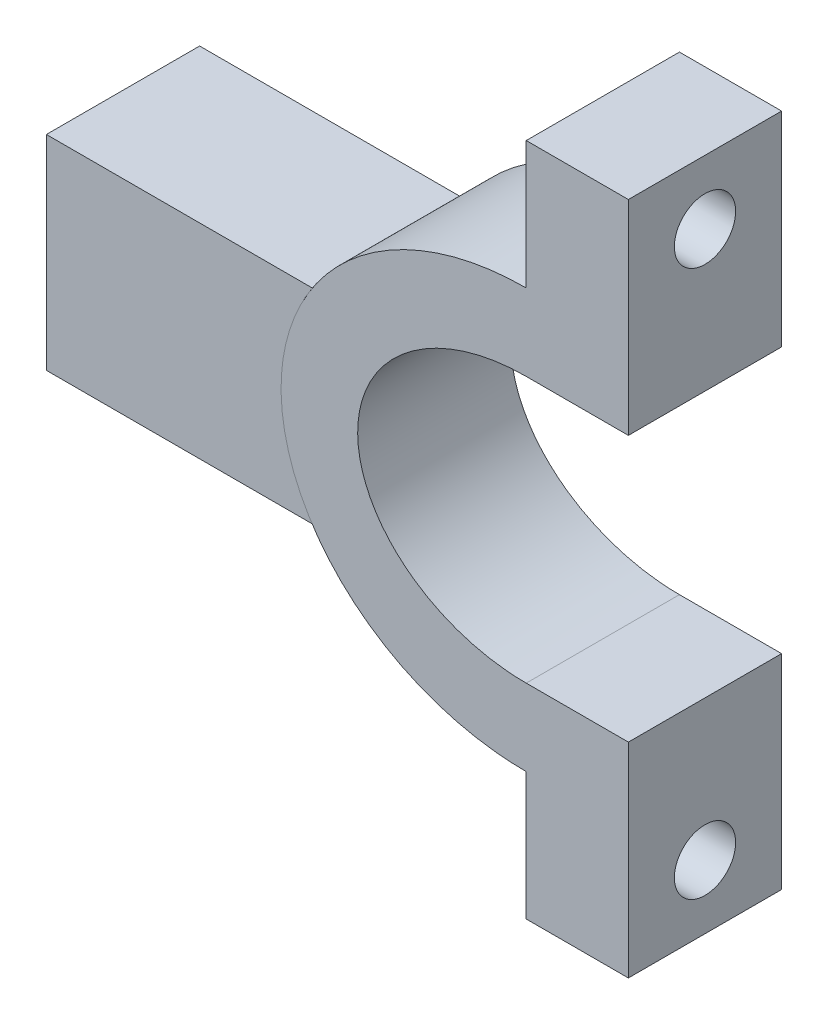
SolidWorks part; units mm, degrees
ref_plane "Front Plane" through (0, 0, 0) normal (0, 0, 1) x (1, 0, 0)
ref_plane "Top Plane" through (0, 0, 0) normal (0, 1, 0) x (1, 0, 0)
ref_plane "Right Plane" through (0, 0, 0) normal (1, 0, 0) x (0, 0, -1)
sketch "Sketch1" plane through (0, 0, 0) normal (0, 0, 1) x (1, 0, 0)
  line L0 (0, 20.5) -> (0, -20.5)
  ellipse E0 centre (0, 0) end of major axis (16.5, 0) minor radius 13
  ellipse E1 centre (0, 0) end of major axis (24, 0) minor radius 20.5
  dimension "D1" = 26
  dimension "D2" = 33
  dimension "D3" = 41
  dimension "D4" = 48
extrude "Boss-Extrude1" add sketch "Sketch1" along normal blind 15 contours L0 E1 E0
ref_plane "Plane1" through (-24, 0, 0) normal (1, 0, 0) x (0, 0, -1)
sketch "Sketch2" plane through (-24, 0, 0) normal (1, 0, 0) x (0, 0, -1)
  line L2 (0.0273, 10) -> (-14.9727, 10)
  line L3 (0.0273, 10) -> (0.0273, -10)
  line L4 (0.0273, -10) -> (-14.9727, -10)
  line L5 (-14.9727, 10) -> (-14.9727, -10)
  line L6 (0.0273, 10) -> (-14.9727, -10) construction
  line L7 (0.0273, -10) -> (-14.9727, 10) construction
  point P2 (-7.4727, 0)
  dimension "D1" = 15
  dimension "D2" = 20
extrude "Boss-Extrude2" add sketch "Sketch2" against normal blind 23 and the other way blind 5
sketch "Sketch3" plane through (0, 0, 0) normal (1, 0, 0) x (0, 0, -1)
  line L0 (0, 0) -> (-15, 0) construction
  line L1 (-15, 13) -> (0, 13)
  line L2 (-15, 13) -> (-15, 33)
  line L3 (-15, 33) -> (0, 33)
  line L4 (0, 13) -> (0, 33)
  line L5 (-15, 13) -> (-15, -13) construction
  line L6 (-15, -33) -> (0, -33)
  line L7 (0, -13) -> (0, -33)
  line L8 (-15, -13) -> (0, -13)
  line L9 (-15, -13) -> (-15, -33)
  dimension "D1" = 20
extrude "Boss-Extrude3" add sketch "Sketch3" along normal blind 10
sketch "Sketch4" plane through (0, 0, 0) normal (-1, 0, 0) x (0, 0, 1)
  line L0 (0, 33) -> (15, 20.5) construction
  line L1 (0, 20.5) -> (15, 33) construction
  line L2 (0, 33) -> (15, 33) construction
  line L3 (0, 0) -> (14.9727, 0) construction
  line L4 (14.9727, 10) -> (14.9727, -10) construction
  circle A0 centre (7.5, 26.75) radius 3
  circle A1 centre (7.5, -26.75) radius 3
  dimension "D1" = 6
extrude "Cut-Extrude1" cut sketch "Sketch4" against normal through all
